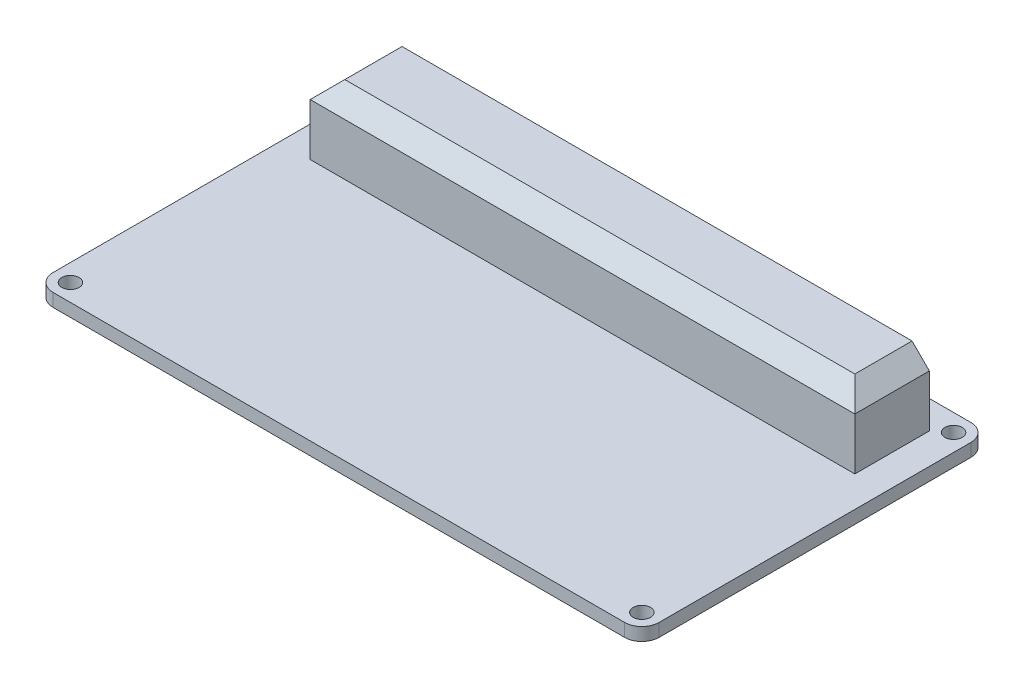
SolidWorks part; units mm, degrees
ref_plane "Front Plane" through (0, 0, 0) normal (0, 0, 1) x (1, 0, 0)
ref_plane "Top Plane" through (0, 0, 0) normal (0, 1, 0) x (1, 0, 0)
ref_plane "Right Plane" through (0, 0, 0) normal (1, 0, 0) x (0, 0, -1)
sketch "Sketch1" plane through (0, 0, 0) normal (0, 1, 0) x (1, 0, 0)
  line L1 (-35, -20) -> (35, -20)
  line L2 (-35, -20) -> (-35, 20)
  line L3 (-35, 20) -> (35, 20)
  line L4 (35, -20) -> (35, 20)
  line L5 (-35, -20) -> (35, 20) construction
  line L6 (-35, 20) -> (35, -20) construction
  point P0 (0, 0)
  dimension "D1" = 70
  dimension "D2" = 40
extrude "Boss-Extrude1" add sketch "Sketch1" along normal blind 1.5
sketch "Sketch2" plane through (0, 1.5, 0) normal (0, 1, 0) x (1, 0, 0)
  line L0 (0, 0) -> (0, 25.4373) construction
  line L2 (-31.4533, 8.1437) -> (31.4533, 8.1437)
  line L3 (-31.4533, 8.1437) -> (-31.4533, 16.7528)
  line L4 (-31.4533, 16.7528) -> (31.4533, 16.7528)
  line L5 (31.4533, 8.1437) -> (31.4533, 16.7528)
  line L6 (-31.4533, 8.1437) -> (31.4533, 16.7528) construction
  line L7 (-31.4533, 16.7528) -> (31.4533, 8.1437) construction
  point P3 (0, 12.4482)
extrude "Boss-Extrude2" add sketch "Sketch2" along normal blind 8
chamfer "Chamfer1" distance 2 angle 45 3 edges at (-31.4533, 9.5, -12.4482) (31.4533, 9.5, -12.4482) (0, 9.5, -8.1437)
sketch "Sketch3" plane through (0, 1.5, 0) normal (0, 1, 0) x (1, 0, 0)
  line L1 (33, -18) -> (-33, -18) construction
  line L2 (33, -18) -> (33, 18) construction
  line L3 (33, 18) -> (-33, 18) construction
  line L4 (-33, -18) -> (-33, 18) construction
  line L5 (33, -18) -> (-33, 18) construction
  line L6 (33, 18) -> (-33, -18) construction
  circle A0 centre (-33, -18) radius 1
  circle A1 centre (-33, 18) radius 1
  circle A2 centre (33, 18) radius 1
  circle A3 centre (33, -18) radius 1
  point P0 (0, 0)
  dimension "D1" = 2
  dimension "D2" = 36
  dimension "D3" = 66
extrude "Cut-Extrude1" cut sketch "Sketch3" against normal through all
fillet "Fillet1" radius 2 4 edges at (-35, 0.75, -20) (35, 0.75, -20) (35, 0.75, 20) (-35, 0.75, 20)
